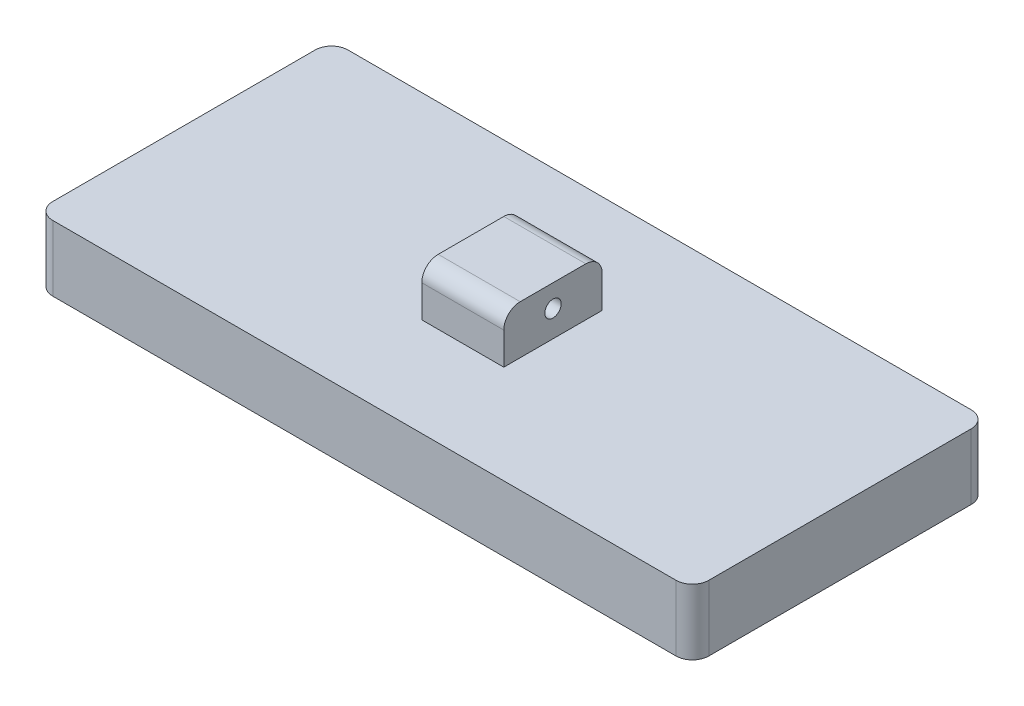
SolidWorks part; units mm, degrees
material "ABS"
ref_plane "Front Plane" through (0, 0, 0) normal (0, 0, 1) x (1, 0, 0)
ref_plane "Top Plane" through (0, 0, 0) normal (0, 1, 0) x (1, 0, 0)
ref_plane "Right Plane" through (0, 0, 0) normal (1, 0, 0) x (0, 0, -1)
sketch "Sketch1" plane through (0, 0, 0) normal (0, 1, 0) x (1, 0, 0)
  line L1 (0, 0) -> (200, 0)
  line L2 (0, 0) -> (0, 90)
  line L3 (0, 90) -> (200, 90)
  line L4 (200, 0) -> (200, 90)
  dimension "D1" = 200
  dimension "D2" = 90
extrude "Boss-Extrude1" add sketch "Sketch1" along normal blind 20
fillet "Fillet1" radius 5 4 edges at (200, 10, 0) (200, 10, -90) (0, 10, -90) (0, 10, 0)
sketch "Sketch2" plane through (0, 20, 0) normal (0, 1, 0) x (1, 0, 0)
  line L0 (195, 90) -> (5, 90) construction
  line L1 (87.5, 30) -> (112.5, 30)
  line L2 (87.5, 30) -> (87.5, 60)
  line L3 (87.5, 60) -> (112.5, 60)
  line L4 (112.5, 30) -> (112.5, 60)
  line L5 (200, 5) -> (200, 85) construction
  point P7 (87.5, 45)
  point P8 (100, 60)
  point P9 (100, 90)
  point P10 (112.5, 45)
  point P13 (200, 45)
  dimension "D1" = 30
  dimension "D4" = 25
extrude "Boss-Extrude2" add sketch "Sketch2" along normal blind 14.8
fillet "Fillet2" radius 5 2 edges at (100, 34.8, -60) (100, 34.8, -30)
sketch "Sketch3" plane through (87.5, 0, 0) normal (-1, 0, 0) x (0, 0, 1)
  line L0 (-60, 20) -> (-30, 20) construction
  line L1 (-49.5611, 28) -> (-47.2805, 24.05)
  line L2 (-47.2805, 24.05) -> (-42.7195, 24.05)
  line L3 (-42.7195, 24.05) -> (-40.4389, 28)
  line L4 (-40.4389, 28) -> (-42.7195, 31.95)
  line L5 (-42.7195, 31.95) -> (-47.2805, 31.95)
  line L6 (-47.2805, 31.95) -> (-49.5611, 28)
  line L7 (-55, 34.8) -> (-35, 34.8) construction
  circle A0 centre (-45, 28) radius 3.95 construction
  point P10 (-45, 20)
  point P14 (-45, 34.8)
  dimension "D1" = 7.9
  dimension "D2" = 8
extrude "Cut-Extrude1" cut sketch "Sketch3" against normal blind 10
sketch "Sketch4" plane through (87.5, 0, 0) normal (-1, 0, 0) x (0, 0, 1)
  circle A0 centre (-45, 28) radius 2.5
  dimension "D1" = 5
extrude "Cut-Extrude2" cut sketch "Sketch4" against normal up to next
